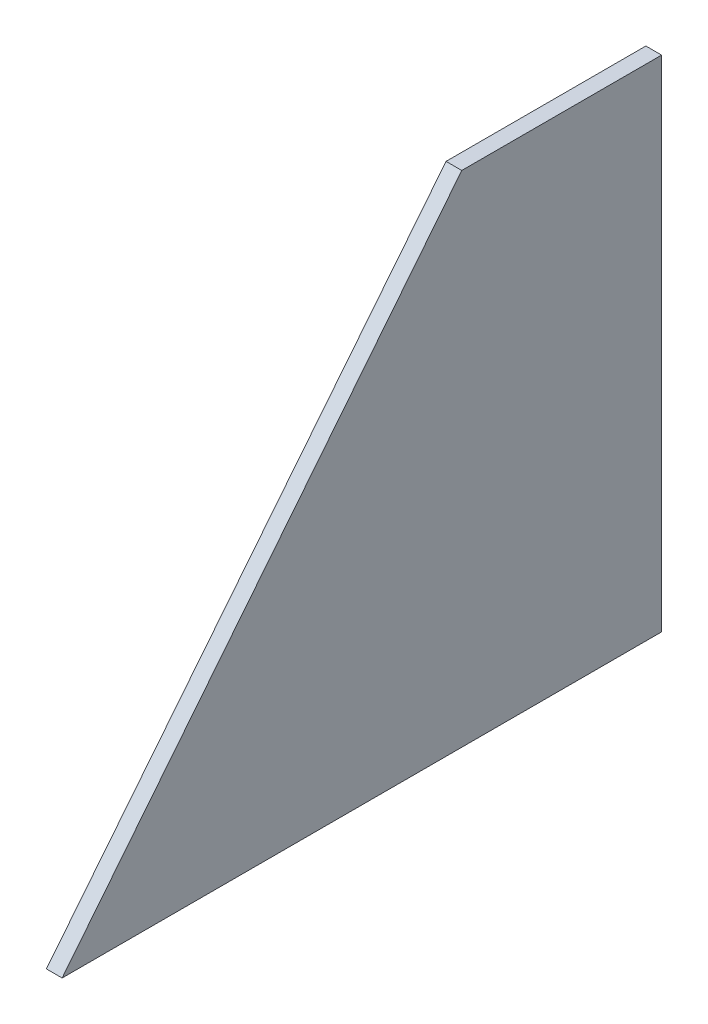
SolidWorks part; units mm, degrees
ref_plane "Front Plane" through (0, 0, 0) normal (0, 0, 1) x (1, 0, 0)
ref_plane "Top Plane" through (0, 0, 0) normal (0, 1, 0) x (1, 0, 0)
ref_plane "Right Plane" through (0, 0, 0) normal (1, 0, 0) x (0, 0, -1)
sketch "Sketch1" plane through (0, 0, 0) normal (1, 0, 0) x (0, 0, -1)
  line L0 (-38.1, -95.25) -> (-190.5, -95.25)
  line L1 (-38.1, -95.25) -> (38.1, -95.25)
  line L2 (-38.1, -95.25) -> (-38.1, 95.25)
  line L3 (-38.1, 95.25) -> (38.1, 95.25)
  line L4 (38.1, -95.25) -> (38.1, 95.25)
  line L5 (-38.1, -95.25) -> (38.1, 95.25) construction
  line L6 (-38.1, 95.25) -> (38.1, -95.25) construction
  line L7 (-190.5, -95.25) -> (-38.1, 95.25)
  point P0 (0, 0)
  dimension "D1" = 152.4
  dimension "D2" = 76.2
  dimension "D3" = 190.5
extrude "Boss-Extrude1" add sketch "Sketch1" along normal blind 6 contours L7 L0 L2 | L1 L4 L3 L2
